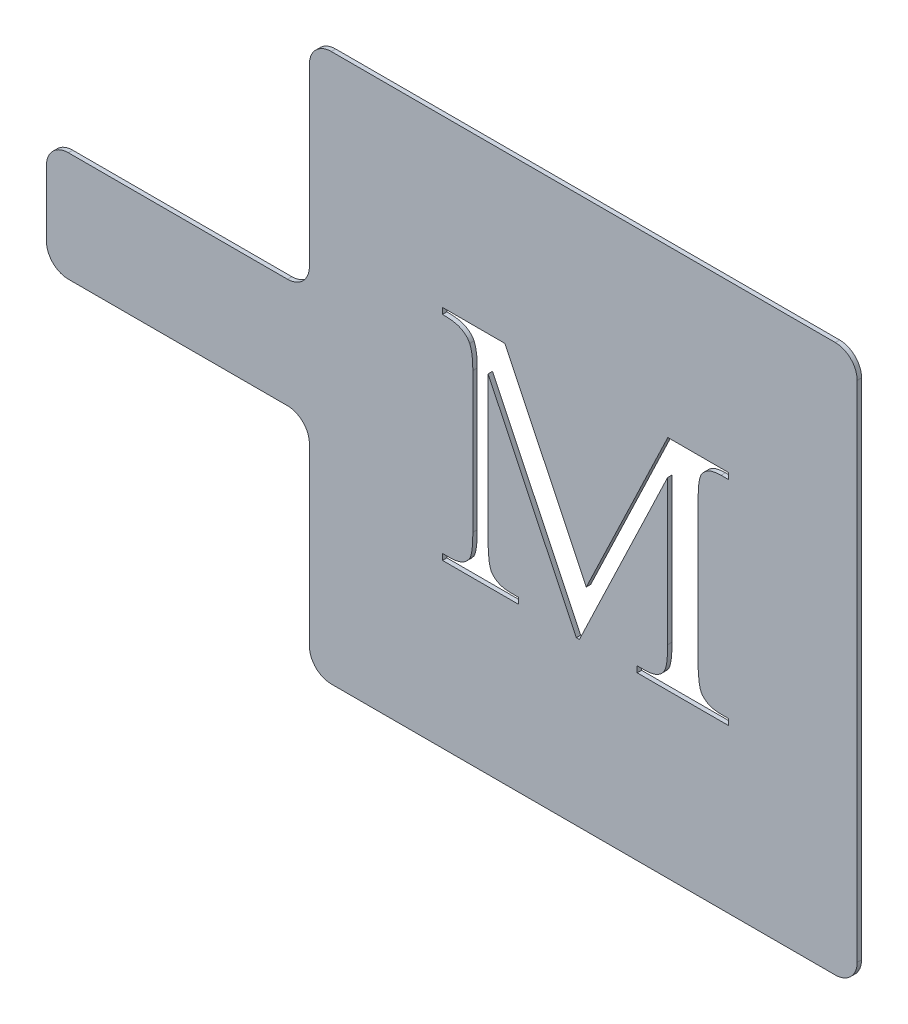
SolidWorks part; units mm, degrees
ref_plane "Front Plane" through (0, 0, 0) normal (0, 0, 1) x (1, 0, 0)
ref_plane "Top Plane" through (0, 0, 0) normal (0, 1, 0) x (1, 0, 0)
ref_plane "Right Plane" through (0, 0, 0) normal (1, 0, 0) x (0, 0, -1)
sketch "Sketch1" plane through (0, 0, 0) normal (0, 0, 1) x (1, 0, 0)
  line L0 (0, 125) -> (250, 125) construction
  line L1 (10, 0) -> (240, 0)
  line L2 (0, 10) -> (0, 90)
  line L3 (10, 250) -> (240, 250)
  line L4 (250, 10) -> (250, 240)
  line L5 (0, 160) -> (0, 240)
  line L6 (-10, 150) -> (-110, 150)
  line L8 (-10, 100) -> (-110, 100)
  line L9 (-120, 140) -> (-120, 110)
  line L10 (0, 150) -> (-120, 100) construction
  line L11 (0, 100) -> (-120, 150) construction
  arc A0 (-110, 150) -> (-120, 140) centre (-110, 140) ccw
  arc A1 (-110, 100) -> (-120, 110) centre (-110, 110) cw
  arc A2 (0, 90) -> (-10, 100) centre (-10, 90) ccw
  arc A3 (-10, 150) -> (0, 160) centre (-10, 160) ccw
  arc A4 (0, 240) -> (10, 250) centre (10, 240) cw
  arc A5 (240, 250) -> (250, 240) centre (240, 240) cw
  arc A6 (240, 0) -> (250, 10) centre (240, 10) ccw
  arc A7 (10, 0) -> (0, 10) centre (10, 10) cw
  point P7 (-60, 125)
  point P26 (0, 250)
  point P29 (250, 250)
  point P34 (0, 0)
  dimension "D5" = 10
  dimension "D1" = 250
  dimension "D2" = 250
  dimension "D3" = 50
  dimension "D4" = 120
extrude "Boss-Extrude1" add sketch "Sketch1" along normal blind 2
sketch "Sketch2" plane through (0, 0, 2) normal (0, 0, 1) x (1, 0, 0)
  text T0 "M" font "Times New Roman" height 100
extrude "Cut-Extrude1" cut sketch "Sketch2" against normal blind 2
